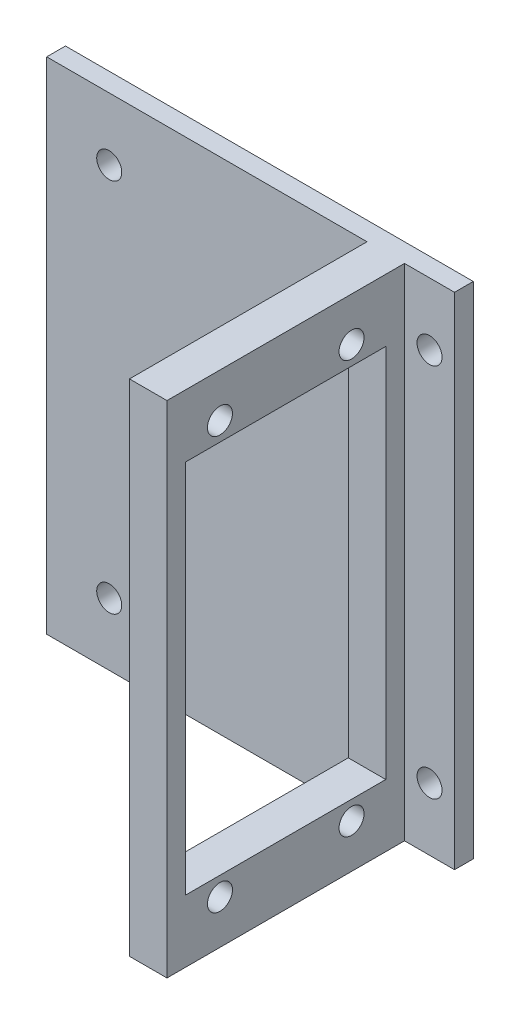
SolidWorks part; units mm, degrees
ref_plane "Alzado" through (0, 0, 0) normal (0, 0, 1) x (1, 0, 0)
ref_plane "Planta" through (0, 0, 0) normal (0, 1, 0) x (1, 0, 0)
ref_plane "Vista lateral" through (0, 0, 0) normal (1, 0, 0) x (0, 0, -1)
sketch "Croquis2" plane through (0, 0, 0) normal (0, 0, 1) x (1, 0, 0)
  line L1 (17.25, 40) -> (-17.25, 40)
  line L2 (17.25, 40) -> (17.25, -40)
  line L3 (17.25, -40) -> (-17.25, -40)
  line L4 (-17.25, 40) -> (-17.25, -40)
  line L5 (17.25, 40) -> (-17.25, -40) construction
  line L6 (17.25, -40) -> (-17.25, 40) construction
  point P0 (0, 0)
  dimension "D1" = 34.5
  dimension "D2" = 80
extrude "Saliente-Extruir2" add sketch "Croquis2" along normal blind 3
sketch "Croquis3" plane through (0, 0, 3) normal (0, 0, 1) x (1, 0, 0)
  line L0 (17.25, 40) -> (-17.25, 40) construction
  line L1 (3.25, 40) -> (9.25, 40)
  line L2 (3.25, 40) -> (3.25, -40)
  line L3 (3.25, -40) -> (9.25, -40)
  line L4 (9.25, 40) -> (9.25, -40)
  line L5 (-17.25, -40) -> (17.25, -40) construction
  line L8 (9.25, -3.0673) -> (17.25, -3.0673) construction
  line L9 (17.25, -40) -> (17.25, 40) construction
  dimension "D1" = 6
  dimension "D2" = 8
extrude "Saliente-Extruir3" add sketch "Croquis3" along normal blind 38
sketch "Croquis7" plane through (9.25, 0, 0) normal (1, 0, 0) x (0, 0, -1)
  line L5 (-6, 30) -> (-38, 30)
  line L6 (-6, 30) -> (-6, -30)
  line L7 (-6, -30) -> (-38, -30)
  line L8 (-38, 30) -> (-38, -30)
  line L9 (-6, 30) -> (-38, -30) construction
  line L10 (-6, -30) -> (-38, 30) construction
  line L11 (-41, 40) -> (-3, 40) construction
  line L12 (-22, 40) -> (-38, 0) construction
  line L13 (-38, 0) -> (-41, 0) construction
  line L14 (-41, -40) -> (-41, 40) construction
  line L15 (-41, 0) -> (-22, -30) construction
  line L18 (-16.2558, -30) -> (-3, 0) construction
  line L19 (-3, -40) -> (-3, 40) construction
  line L20 (-3, 0) -> (-6, 0) construction
  point P0 (-22, 0)
  point P1 (-22, 0)
  point P2 (-22, 0)
  dimension "D1" = 60
  dimension "D2" = 32
extrude "Cortar-Extruir3" cut sketch "Croquis7" against normal through all both and the other way through all
sketch "Croquis5" plane through (3.25, 0, 0) normal (-1, 0, 0) x (0, 0, 1)
  line L3 (0, 0) -> (41, 0) construction
  line L5 (41, 40) -> (41, -40) construction
  line L6 (11.475, 33) -> (32.525, 33) construction
  line L7 (22, 33) -> (22, 40) construction
  line L8 (41, 40) -> (3, 40) construction
  line L9 (11.475, -33) -> (32.525, -33) construction
  line L10 (32.525, -33) -> (22, -33) construction
  line L11 (22, -33) -> (22, -40) construction
  line L12 (41, -40) -> (3, -40) construction
  circle A4 centre (11.475, 33) radius 2
  circle A5 centre (32.525, 33) radius 2
  circle A6 centre (32.525, -33) radius 2
  circle A7 centre (11.475, -33) radius 2
  dimension "D2" = 21.05
  dimension "D3" = 33
  dimension "D1" = 4
extrude "Cortar-Extruir2" cut sketch "Croquis5" against normal through all
sketch "Croquis8" plane through (-17.25, -40, 0) normal (1, 0, 0) x (0, 0, -1)
  line L1 (0, 80) -> (-3, 80)
  line L2 (0, 80) -> (0, 0)
  line L3 (0, 0) -> (-3, 0)
  line L4 (-3, 80) -> (-3, 0)
extrude "Saliente-Extruir5" add sketch "Croquis8" against normal blind 30.74
sketch "Croquis9" plane through (0, 0, 3) normal (0, 0, 1) x (1, 0, 0)
  line L0 (0, 0) -> (-47.99, 0) construction
  line L1 (-47.99, 40) -> (-47.99, -40) construction
  line L2 (-37.99, 30) -> (-47.99, 30) construction
  line L3 (-47.99, 30) -> (-47.99, 40) construction
  line L4 (-47.99, 40) -> (-37.99, 40) construction
  line L5 (3.25, 40) -> (-47.99, 40) construction
  line L6 (-37.99, 40) -> (-37.99, 30) construction
  circle A0 centre (-37.99, 30) radius 2
  circle A1 centre (-37.99, -30) radius 2
  dimension "D1" = 4
  dimension "D2" = 10
extrude "Cortar-Extruir4" cut sketch "Croquis9" against normal blind 30.74
sketch "Croquis10" plane through (0, 0, 3) normal (0, 0, 1) x (1, 0, 0)
  line L0 (-37.99, 30) -> (17.25, 30) construction
  line L1 (17.25, -40) -> (17.25, 40) construction
  line L2 (17.25, 30) -> (-37.99, -30) construction
  line L3 (-37.99, -30) -> (14.0896, -30) construction
  line L4 (14.0896, -30) -> (14.0896, -25.7291) construction
  line L5 (13.25, 30) -> (13.25, -30) construction
  circle A0 centre (13.25, 30) radius 2
  circle A1 centre (13.25, -30) radius 2
  dimension "D1" = 4
  dimension "D2" = 4
  dimension "D3" = 4
extrude "Cortar-Extruir5" cut sketch "Croquis10" against normal blind 194
